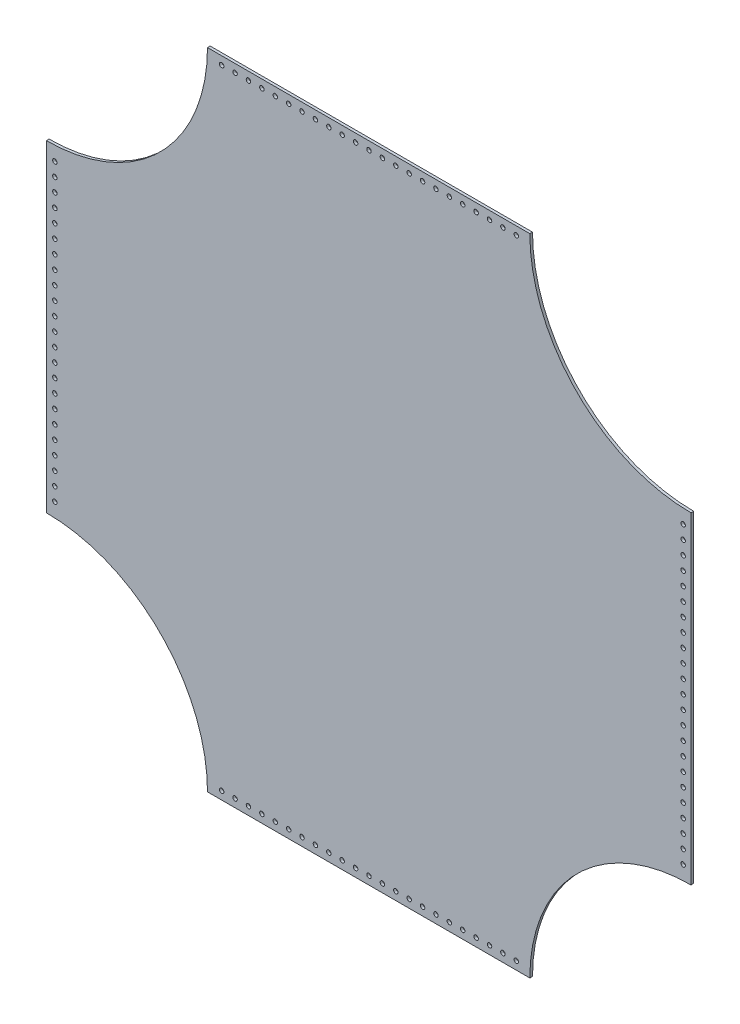
SolidWorks part; units mm, degrees
material "Plain Carbon Steel"
ref_plane "Front Plane" through (0, 0, 0) normal (0, 0, 1) x (1, 0, 0)
ref_plane "Top Plane" through (0, 0, 0) normal (0, 1, 0) x (1, 0, 0)
ref_plane "Right Plane" through (0, 0, 0) normal (1, 0, 0) x (0, 0, -1)
sketch "Sketch1" plane through (0, 0, 0) normal (0, 0, 1) x (1, 0, 0)
  line L0 (-361, 180.5) -> (-361, -180.5)
  line L1 (-381, -381) -> (381, -381) construction
  line L2 (-381, -381) -> (-381, 381) construction
  line L3 (-381, 381) -> (381, 381) construction
  line L4 (381, -381) -> (381, 381) construction
  line L5 (-381, -381) -> (381, 381) construction
  line L6 (-381, 381) -> (381, -381) construction
  line L7 (-361, -361) -> (361, -361) construction
  line L8 (-361, -361) -> (-361, 361) construction
  line L9 (-361, 361) -> (361, 361) construction
  line L10 (361, -361) -> (361, 361) construction
  line L11 (0, 361) -> (0, -361) construction
  line L12 (-361, 0) -> (361, 0) construction
  line L13 (-180.5, -361) -> (180.5, -361)
  line L14 (361, -180.5) -> (361, 180.5)
  line L15 (180.5, 361) -> (-180.5, 361)
  line L16 (-361, 361) -> (-361, 0) construction
  line L17 (-361, 361) -> (-361, 0)
  arc A0 (-361, 180.5) -> (-180.5, 361) centre (-361, 361) ccw
  arc A1 (180.5, 361) -> (361, 180.5) centre (361, 361) ccw
  arc A2 (361, -180.5) -> (180.5, -361) centre (361, -361) ccw
  arc A3 (-361, -180.5) -> (-180.5, -361) centre (-361, -361) cw
  point P0 (0, 0)
  point P7 (0, 0)
  point P18 (-361, 381)
  point P21 (-361, 180.5)
  dimension "D1" = 762
  dimension "D2" = 762
  dimension "D3" = 20
extrude "Boss-Extrude1" add sketch "Sketch1" along normal blind 3 contours L0 A3 L13 A2 L14 A1 L15 A0
sketch "Sketch2" plane through (0, 0, 3) normal (0, 0, 1) x (1, 0, 0)
  line L0 (180.5, 361) -> (-180.5, 361) construction
  line L1 (-361, -361) -> (361, -361) construction
  line L2 (-361, -361) -> (-361, 361) construction
  line L3 (-361, 361) -> (361, 361) construction
  line L4 (361, -361) -> (361, 361) construction
  line L5 (-361, -361) -> (361, 361) construction
  line L6 (-361, 361) -> (361, -361) construction
  line L7 (-361, 180.5) -> (-361, -180.5) construction
  line L8 (233.3672, -233.3672) -> (-233.3672, -233.3672) construction
  line L9 (233.3672, -233.3672) -> (233.3672, 233.3672) construction
  line L10 (-233.3672, -233.3672) -> (-233.3672, 233.3672) construction
  line L11 (233.3672, 233.3672) -> (-233.3672, 233.3672) construction
  line L12 (-361, 0) -> (361, 0) construction
  arc A2 (361, -180.5) -> (180.5, -361) centre (361, -361) ccw construction
  arc A3 (-180.5, -361) -> (-361, -180.5) centre (-361, -361) ccw construction
  circle A4 centre (-351.5, 0) radius 2.5
  circle A5 centre (-351.5, 15) radius 2.5
  circle A6 centre (-351.5, 30) radius 2.5
  circle A7 centre (-351.5, 45) radius 2.5
  circle A8 centre (-351.5, 60) radius 2.5
  circle A9 centre (-351.5, 75) radius 2.5
  circle A10 centre (-351.5, 90) radius 2.5
  circle A11 centre (-351.5, 105) radius 2.5
  circle A12 centre (-351.5, 120) radius 2.5
  circle A13 centre (-351.5, 135) radius 2.5
  circle A14 centre (-351.5, 150) radius 2.5
  circle A15 centre (-351.5, 165) radius 2.5
  circle A16 centre (-351.5, -15) radius 2.5
  circle A17 centre (-351.5, -30) radius 2.5
  circle A18 centre (-351.5, -45) radius 2.5
  circle A19 centre (-351.5, -60) radius 2.5
  circle A20 centre (-351.5, -75) radius 2.5
  circle A21 centre (-351.5, -90) radius 2.5
  circle A22 centre (-351.5, -105) radius 2.5
  circle A23 centre (-351.5, -120) radius 2.5
  circle A24 centre (-351.5, -135) radius 2.5
  circle A25 centre (-351.5, -150) radius 2.5
  circle A26 centre (-351.5, -165) radius 2.5
  circle A27 centre (-165, 351.5) radius 2.5
  circle A28 centre (-150, 351.5) radius 2.5
  circle A29 centre (-135, 351.5) radius 2.5
  circle A30 centre (-120, 351.5) radius 2.5
  circle A31 centre (-105, 351.5) radius 2.5
  circle A32 centre (-90, 351.5) radius 2.5
  circle A33 centre (-75, 351.5) radius 2.5
  circle A34 centre (-60, 351.5) radius 2.5
  circle A35 centre (-30, 351.5) radius 2.5
  circle A36 centre (-45, 351.5) radius 2.5
  circle A37 centre (-15, 351.5) radius 2.5
  circle A38 centre (0, 351.5) radius 2.5
  circle A39 centre (15, 351.5) radius 2.5
  circle A40 centre (30, 351.5) radius 2.5
  circle A41 centre (45, 351.5) radius 2.5
  circle A42 centre (60, 351.5) radius 2.5
  circle A43 centre (75, 351.5) radius 2.5
  circle A44 centre (90, 351.5) radius 2.5
  circle A45 centre (105, 351.5) radius 2.5
  circle A46 centre (120, 351.5) radius 2.5
  circle A47 centre (135, 351.5) radius 2.5
  circle A48 centre (150, 351.5) radius 2.5
  circle A49 centre (165, 351.5) radius 2.5
  circle A50 centre (351.5, 165) radius 2.5
  circle A51 centre (351.5, 150) radius 2.5
  circle A52 centre (351.5, 135) radius 2.5
  circle A53 centre (351.5, 120) radius 2.5
  circle A54 centre (351.5, 105) radius 2.5
  circle A55 centre (351.5, 90) radius 2.5
  circle A56 centre (351.5, 75) radius 2.5
  circle A57 centre (351.5, 60) radius 2.5
  circle A58 centre (351.5, 30) radius 2.5
  circle A59 centre (351.5, 45) radius 2.5
  circle A60 centre (351.5, 15) radius 2.5
  circle A61 centre (351.5, 0) radius 2.5
  circle A62 centre (351.5, -15) radius 2.5
  circle A63 centre (351.5, -30) radius 2.5
  circle A64 centre (351.5, -45) radius 2.5
  circle A65 centre (351.5, -60) radius 2.5
  circle A66 centre (351.5, -75) radius 2.5
  circle A67 centre (351.5, -90) radius 2.5
  circle A68 centre (351.5, -105) radius 2.5
  circle A69 centre (351.5, -120) radius 2.5
  circle A70 centre (351.5, -135) radius 2.5
  circle A71 centre (351.5, -150) radius 2.5
  circle A72 centre (351.5, -165) radius 2.5
  circle A73 centre (165, -351.5) radius 2.5
  circle A74 centre (150, -351.5) radius 2.5
  circle A75 centre (135, -351.5) radius 2.5
  circle A76 centre (120, -351.5) radius 2.5
  circle A77 centre (105, -351.5) radius 2.5
  circle A78 centre (90, -351.5) radius 2.5
  circle A79 centre (75, -351.5) radius 2.5
  circle A80 centre (60, -351.5) radius 2.5
  circle A81 centre (30, -351.5) radius 2.5
  circle A82 centre (45, -351.5) radius 2.5
  circle A83 centre (15, -351.5) radius 2.5
  circle A84 centre (0, -351.5) radius 2.5
  circle A85 centre (-15, -351.5) radius 2.5
  circle A86 centre (-30, -351.5) radius 2.5
  circle A87 centre (-45, -351.5) radius 2.5
  circle A88 centre (-60, -351.5) radius 2.5
  circle A89 centre (-75, -351.5) radius 2.5
  circle A90 centre (-90, -351.5) radius 2.5
  circle A91 centre (-105, -351.5) radius 2.5
  circle A92 centre (-120, -351.5) radius 2.5
  circle A93 centre (-135, -351.5) radius 2.5
  circle A94 centre (-150, -351.5) radius 2.5
  circle A95 centre (-165, -351.5) radius 2.5
  point P0 (0, 0)
  point P24 (0, 0)
  point P26 (0, 0)
  point P48 (0, 0)
  point P210 (0, 0)
  dimension "D1" = 9.5
  dimension "D2" = 5
  dimension "D8" = 186.5
  dimension "D4" = 15
  dimension "D6" = 15
  dimension "D9" = 186.5
  dimension "D3" = 12
  dimension "D5" = 12
  dimension "D7" = 4
extrude "Cut-Extrude1" cut sketch "Sketch2" against normal blind 3 contours A15 | A14 | A13 | A12 | A11 | A10 | A9 | A8 | A7 | A6 | A5 | A4 | A16 | A17 | A26 | A25 | A24 | A23 | A18 | A19 | A20 | A21 | A22
pattern_circular "CirPattern1" count 4 every 90 about axis through (0.3793, 0, 0) along (0, 0, 1) of "Cut-Extrude1"
sketch "Sketch3" plane through (0, 0, 3) normal (0, 0, 1) x (1, 0, 0)
  circle A0 centre (0, 0) radius 31.1394
equation "\"a\"= \"SW-Mass\""
